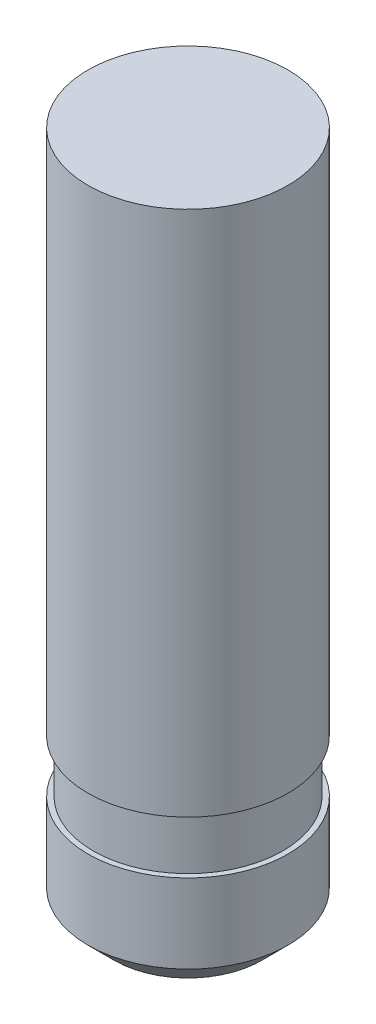
SolidWorks part; units mm, degrees
ref_plane "Front Plane" through (0, 0, 0) normal (0, 0, 1) x (1, 0, 0)
ref_plane "Top Plane" through (0, 0, 0) normal (0, 1, 0) x (1, 0, 0)
ref_plane "Right Plane" through (0, 0, 0) normal (1, 0, 0) x (0, 0, -1)
sketch "Sketch1" plane through (0, 0, 0) normal (0, 1, 0) x (1, 0, 0)
  circle A0 centre (0, 0) radius 1.9
  dimension "D1" = 3.8
extrude "Boss-Extrude1" add sketch "Sketch1" along normal blind 2 contours A0
sketch "Sketch2" plane through (0, 2, 0) normal (0, 1, 0) x (1, 0, 0)
  circle A0 centre (0, 0) radius 1.8
  dimension "D1" = 3.6
extrude "Boss-Extrude2" add sketch "Sketch2" along normal blind 1
sketch "Sketch3" plane through (0, 3, 0) normal (0, 1, 0) x (1, 0, 0)
  circle A0 centre (0, 0) radius 1.9
extrude "Boss-Extrude3" add sketch "Sketch3" along normal blind 10
chamfer "Chamfer1" distance 0.5 angle 45 1 edges at (0, 0, 1.9)
